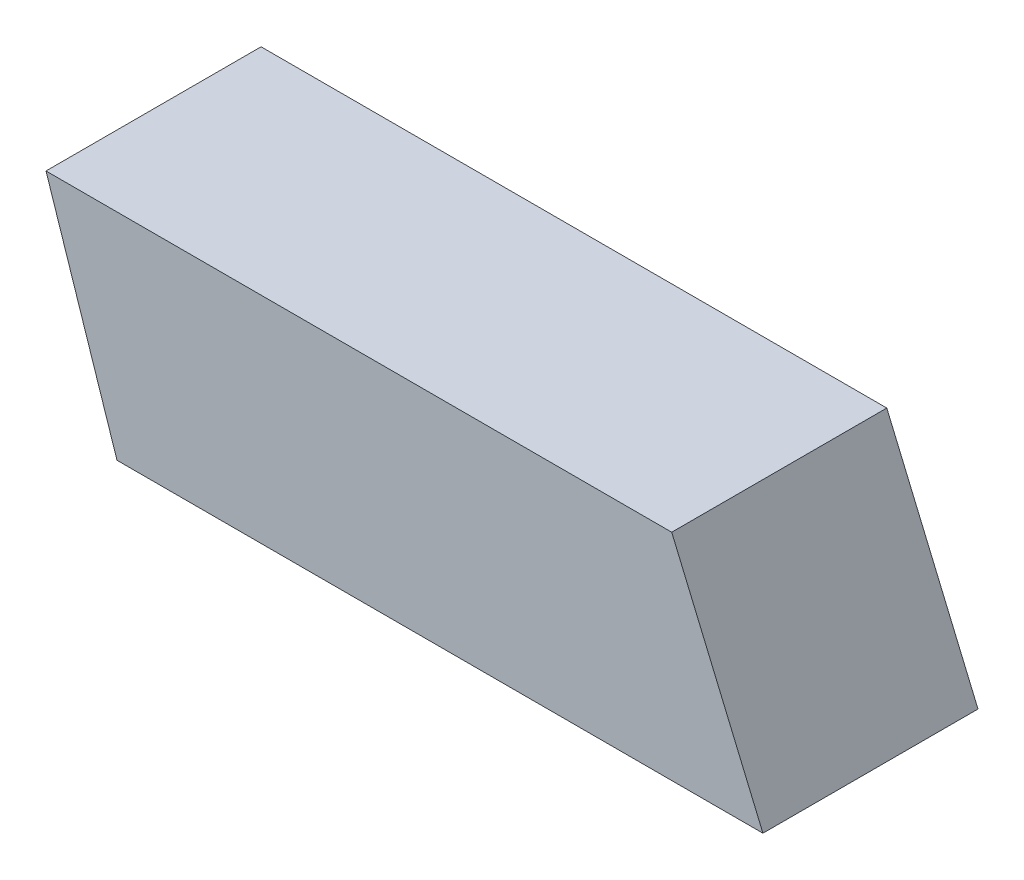
SolidWorks part; units mm, degrees
ref_plane "前视基准面" through (0, 0, 0) normal (0, 0, 1) x (1, 0, 0)
ref_plane "上视基准面" through (0, 0, 0) normal (0, 1, 0) x (1, 0, 0)
ref_plane "右视基准面" through (0, 0, 0) normal (1, 0, 0) x (0, 0, -1)
sketch "草图2" plane through (0, 0, 0) normal (1, 0, 0) x (0, 0, -1)
  line L1 (-3, 3) -> (3, 3)
  line L2 (-3, 3) -> (-3, -3)
  line L3 (-3, -3) -> (3, -3)
  line L4 (3, 3) -> (3, -3)
  line L5 (-3, 3) -> (3, -3) construction
  line L6 (-3, -3) -> (3, 3) construction
  point P0 (0, 0)
  dimension "D1" = 6
  dimension "D2" = 6
extrude "凸台-拉伸1" add sketch "草图2" along normal blind 20
sketch "草图3" plane through (0, 0, 3) normal (0, 0, 1) x (1, 0, 0)
  line L0 (0, 3) -> (1.9808, -3)
  line L1 (20, -3) -> (0, -3) construction
  line L2 (1.9808, -3) -> (0, -3)
  line L3 (0, 3) -> (0, -3) construction
  line L4 (0, 3) -> (0, -3)
  line L5 (17.4554, 3) -> (20, -3)
  line L6 (20, 3) -> (0, 3) construction
  line L7 (20, -3) -> (20, 3)
  line L8 (20, 3) -> (17.4554, 3)
extrude "切除-拉伸1" cut sketch "草图3" against normal blind 10
